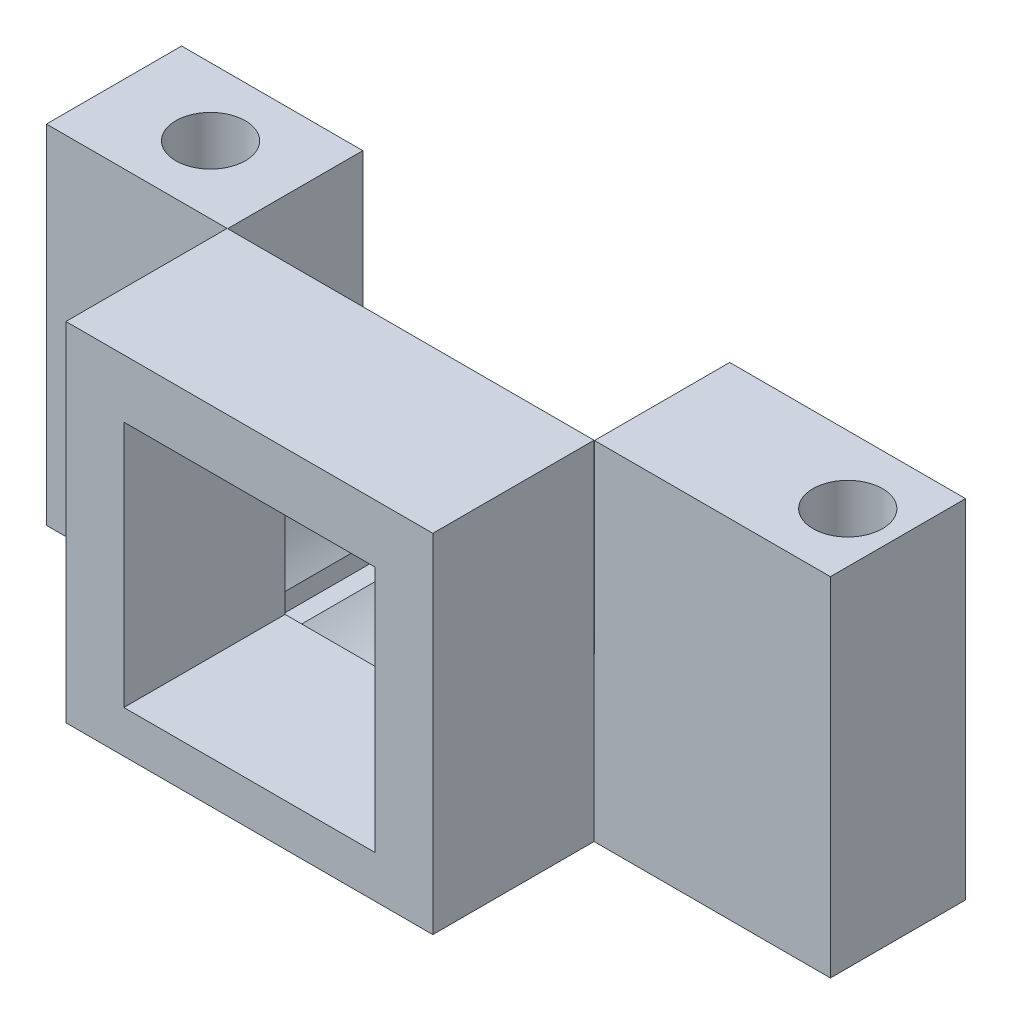
SolidWorks part; units mm, degrees
ref_plane "Front Plane" through (0, 0, 0) normal (0, 0, 1) x (1, 0, 0)
ref_plane "Top Plane" through (0, 0, 0) normal (0, 1, 0) x (1, 0, 0)
ref_plane "Right Plane" through (0, 0, 0) normal (1, 0, 0) x (0, 0, -1)
sketch "Sketch1" plane through (0, 0, 0) normal (0, 0, 1) x (1, 0, 0)
  line L0 (-0.5, 1.7) -> (40.1, 1.7)
  line L12 (8.8843, 20.0309) -> (27.8843, 20.0309)
  line L13 (8.8843, 20.0309) -> (8.8843, 10.1196)
  line L14 (8.8843, 10.1196) -> (27.8843, 10.1196)
  line L15 (27.8843, 20.0309) -> (27.8843, 10.1196)
  line L16 (-0.5, 19.7) -> (40.1, 19.7)
  line L17 (-0.5, 19.7) -> (-0.5, 1.7)
  line L18 (40.1, 19.7) -> (40.1, 1.7)
  line L19 (11.6843, 16.9357) -> (25.0843, 16.9357)
  line L20 (11.6843, 16.9357) -> (11.6843, 3.7857)
  line L21 (11.6843, 3.7857) -> (25.0843, 3.7857)
  line L22 (25.0843, 16.9357) -> (25.0843, 3.7857)
  circle A1 centre (18.3887, 10.3631) radius 8.75
extrude "Boss-Extrude1" add sketch "Sketch1" along normal blind 7 contours A1 L14 L13 L16 L17 L0 L21 L20 | A1 L0 L18 L16 L15 L14 L22 L21
sketch "Sketch2" plane through (0, 0, 7) normal (0, 0, 1) x (1, 0, 0)
  line L0 (8.86, 19.7) -> (27.8604, 19.7)
  line L1 (8.86, 19.7) -> (8.86, 1.7)
  line L2 (8.86, 1.7) -> (27.8604, 1.7)
  line L3 (27.8604, 19.7) -> (27.8604, 1.7)
  line L4 (11.8604, 16.6875) -> (24.8604, 16.6875)
  line L5 (11.8604, 16.6875) -> (11.8604, 3.8875)
  line L6 (11.8604, 3.8875) -> (24.8604, 3.8875)
  line L7 (24.8604, 16.6875) -> (24.8604, 3.8875)
extrude "Boss-Extrude2" add sketch "Sketch2" along normal blind 8.35
sketch "Sketch3" plane through (0, 19.7, 0) normal (0, 1, 0) x (1, 0, 0)
  circle A0 centre (4.5, -3.5) radius 1.8
  circle A1 centre (37.5, -3.5) radius 1.8
extrude "Cut-Extrude1" cut sketch "Sketch3" against normal through all
